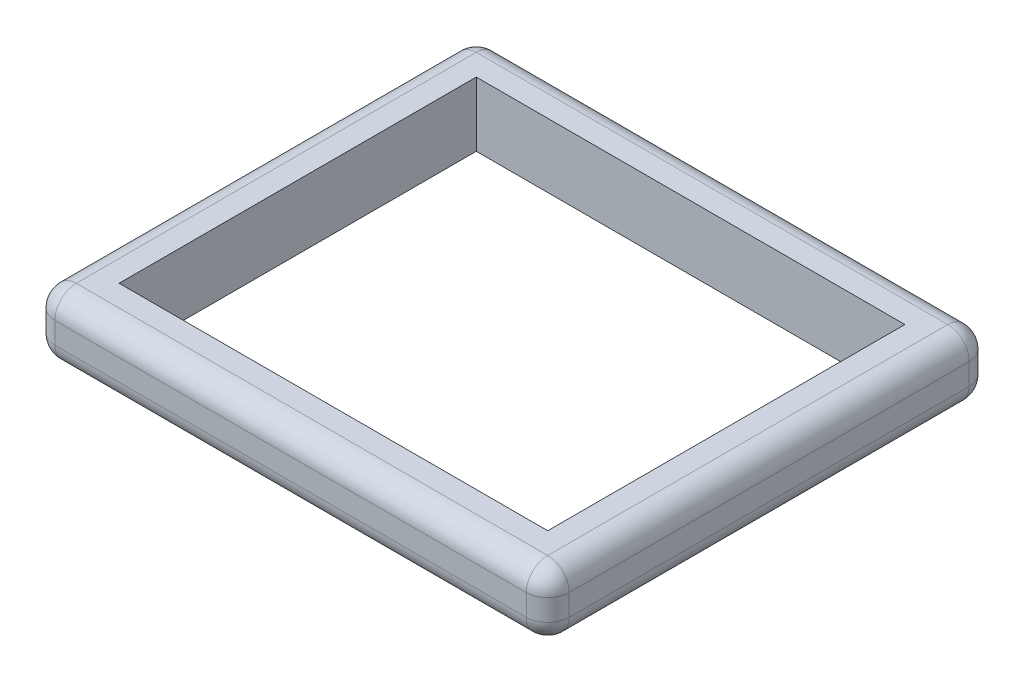
SolidWorks part; units mm, degrees
ref_plane "Front Plane" through (0, 0, 0) normal (0, 0, 1) x (1, 0, 0)
ref_plane "Top Plane" through (0, 0, 0) normal (0, 1, 0) x (1, 0, 0)
ref_plane "Right Plane" through (0, 0, 0) normal (1, 0, 0) x (0, 0, -1)
sketch "Sketch1" plane through (0, 0, 0) normal (0, 1, 0) x (1, 0, 0)
  line L5 (-381, 317.5) -> (381, 317.5)
  line L6 (-381, 317.5) -> (-381, -317.5)
  line L11 (-381, -317.5) -> (381, -317.5)
  line L12 (381, 317.5) -> (381, -317.5)
  line L13 (-381, 317.5) -> (381, -317.5) construction
  line L14 (-381, -317.5) -> (381, 317.5) construction
  line L15 (-457.2, 393.7) -> (457.2, 393.7)
  line L16 (-457.2, 393.7) -> (-457.2, -393.7)
  line L17 (-457.2, -393.7) -> (457.2, -393.7)
  line L18 (457.2, 393.7) -> (457.2, -393.7)
  line L19 (-457.2, 393.7) -> (457.2, -393.7) construction
  line L20 (-457.2, -393.7) -> (457.2, 393.7) construction
  point P0 (0, 0)
  point P1 (0, 0)
  point P5 (0, 0)
  point P8 (0, 0)
  dimension "D1" = 635
  dimension "D2" = 762
  dimension "D3" = 787.4
  dimension "D4" = 914.4
extrude "Boss-Extrude1" add sketch "Sketch1" along normal blind 114.3
sketch "Sketch3" plane through (0, 0, 317.5) normal (0, 0, -1) x (-1, 0, 0)
  line L0 (-36.0135, 74.4613) -> (65.6865, 74.4613)
  line L1 (241.3, 74.4613) -> (-241.3, 74.4613) construction
fillet "Fillet2" radius 38.1 4 edges at (457.2, 57.15, 393.7) (-457.2, 57.15, 393.7) (-457.2, 57.15, -393.7) (457.2, 57.15, -393.7)
fillet "Fillet3" radius 38.1 8 edges at (446.0408, 114.3, 382.5408) (0, 114.3, 393.7) (-446.0408, 114.3, 382.5408) (-457.2, 114.3, 0) (-446.0408, 114.3, -382.5408) (0, 114.3, -393.7) (446.0408, 114.3, -382.5408) (457.2, 114.3, 0)
fillet "Fillet4" radius 38.1 8 edges at (446.0408, 0, 382.5408) (0, 0, 393.7) (-446.0408, 0, 382.5408) (-457.2, 0, 0) (-446.0408, 0, -382.5408) (0, 0, -393.7) (446.0408, 0, -382.5408) (457.2, 0, 0)
sketch "Sketch4" plane through (0, 0, -317.5) normal (0, 0, 1) x (1, 0, 0)
  line L0 (-52.6776, 53.975) -> (-16.7869, 53.975) construction
  line L1 (273.05, 53.975) -> (-273.05, 53.975) construction
